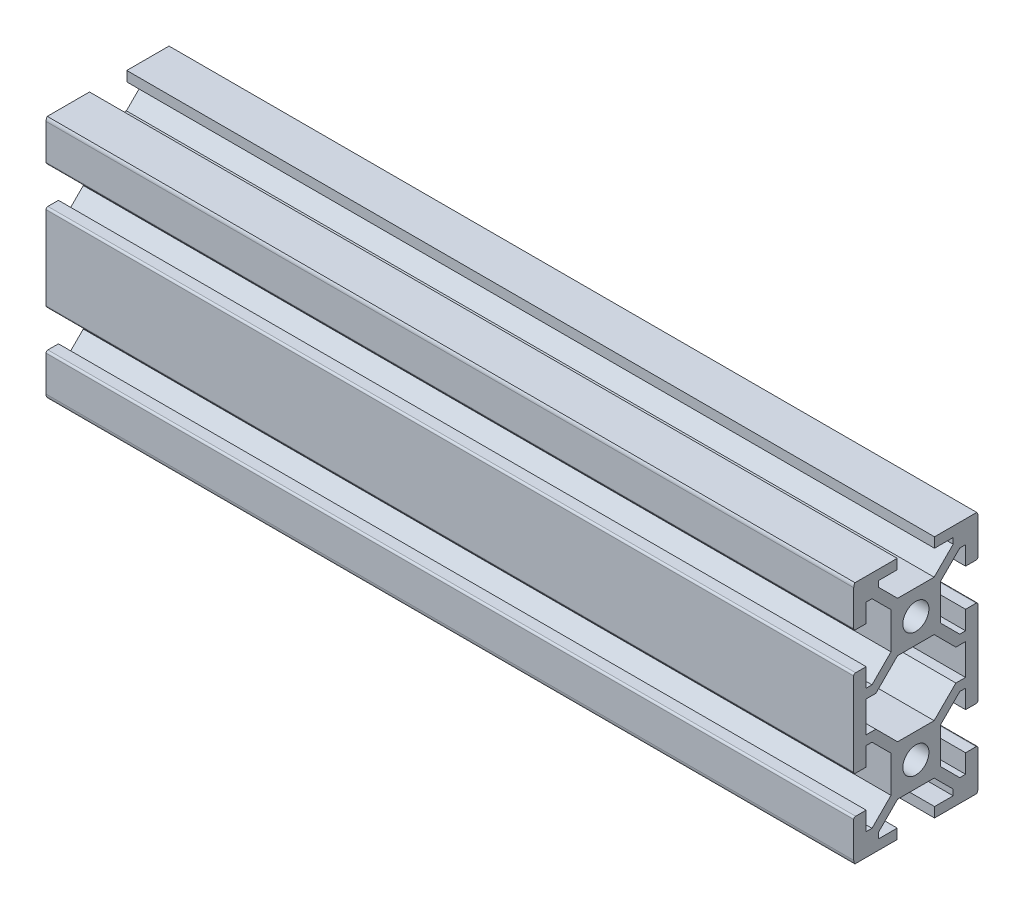
SolidWorks part; units mm, degrees
ref_plane "Front Plane" through (0, 0, 0) normal (0, 0, 1) x (1, 0, 0)
ref_plane "Top Plane" through (0, 0, 0) normal (0, 1, 0) x (1, 0, 0)
ref_plane "Right Plane" through (0, 0, 0) normal (1, 0, 0) x (0, 0, -1)
sketch "Sketch1" plane through (0, 0, 0) normal (0, 1, 0) x (1, 0, 0)
  line L0 (0, 0) -> (130, 0)
  dimension "D1" = 130
other "Seri 5 (20,40) 20X40S5(2)"
ref_plane "Plane1" through (0, 0, 0) normal (1, 0, 0) x (0, 0, -1)
sketch "草图1" plane through (0, 0, 0) normal (1, 0, 0) x (0, 0, -1)
  line L0 (-10, 19) -> (-10, 13.3)
  line L1 (-9.7, 13) -> (-8, 13)
  line L2 (-8, 13) -> (-8, 16)
  line L3 (-8, 16) -> (-7.0607, 16)
  line L4 (-7.0607, 16) -> (-4, 12.9393)
  line L5 (-4, 12.9393) -> (-4, 7.0607)
  line L6 (-4, 7.0607) -> (-7.0607, 4)
  line L7 (-7.0607, 4) -> (-8, 4)
  line L8 (-8, 4) -> (-8, 7)
  line L9 (-8, 7) -> (-9.7, 7)
  line L10 (-10, 6.7) -> (-10, -6.7)
  line L11 (-9.7, -7) -> (-8, -7)
  line L12 (-8, -7) -> (-8, -4)
  line L13 (-8, -4) -> (-7.0607, -4)
  line L14 (-7.0607, -4) -> (-4, -7.0607)
  line L15 (-4, -7.0607) -> (-4, -12.9393)
  line L16 (-4, -12.9393) -> (-7.0607, -16)
  line L17 (-7.0607, -16) -> (-8, -16)
  line L18 (-8, -16) -> (-8, -13)
  line L19 (-8, -13) -> (-9.7, -13)
  line L20 (-10, -13.3) -> (-10, -19)
  line L21 (-9.8, -19.6) -> (-3, -19.6)
  line L22 (-3, -19.6) -> (-3, -18)
  line L23 (-3, -18) -> (-6, -18)
  line L24 (-6, -18) -> (-6, -17.0607)
  line L25 (-6, -17.0607) -> (-2.9393, -14)
  line L26 (-2.9393, -14) -> (2.9393, -14)
  line L27 (2.9393, -14) -> (6, -17.0607)
  line L28 (6, -17.0607) -> (6, -18)
  line L29 (6, -18) -> (3, -18)
  line L30 (3, -18) -> (3, -19.6)
  line L31 (3, -19.6) -> (9.8, -19.6)
  line L32 (10, -19) -> (10, -13.3)
  line L33 (9.7, -13) -> (8, -13)
  line L34 (8, -13) -> (8, -16)
  line L35 (8, -16) -> (7.0607, -16)
  line L36 (7.0607, -16) -> (4, -12.9393)
  line L37 (4, -12.9393) -> (4, -7.0607)
  line L38 (4, -7.0607) -> (7.0607, -4)
  line L39 (7.0607, -4) -> (8, -4)
  line L40 (8, -4) -> (8, -7)
  line L41 (8, -7) -> (9.7, -7)
  line L42 (10, -6.7) -> (10, 6.7)
  line L43 (9.7, 7) -> (8, 7)
  line L44 (8, 7) -> (8, 4)
  line L45 (8, 4) -> (7.0607, 4)
  line L46 (7.0607, 4) -> (4, 7.0607)
  line L47 (4, 7.0607) -> (4, 12.9393)
  line L48 (4, 12.9393) -> (7.0607, 16)
  line L49 (7.0607, 16) -> (8, 16)
  line L50 (8, 16) -> (8, 13)
  line L51 (8, 13) -> (9.7, 13)
  line L52 (10, 13.3) -> (10, 19)
  line L53 (9.8, 19.6) -> (3, 19.6)
  line L54 (3, 19.6) -> (3, 18)
  line L55 (3, 18) -> (6, 18)
  line L56 (6, 18) -> (6, 17.0607)
  line L57 (6, 17.0607) -> (2.9393, 14)
  line L58 (2.9393, 14) -> (-2.9393, 14)
  line L59 (-2.9393, 14) -> (-6, 17.0607)
  line L60 (-6, 17.0607) -> (-6, 18)
  line L61 (-6, 18) -> (-3, 18)
  line L62 (-3, 18) -> (-3, 19.6)
  line L63 (-3, 19.6) -> (-9.8, 19.6)
  line L64 (-8, -2.5) -> (-6.4393, -2.5)
  line L65 (-6.4393, -2.5) -> (-2.9393, -6)
  line L66 (-2.9393, -6) -> (2.9393, -6)
  line L67 (2.9393, -6) -> (6.4393, -2.5)
  line L68 (6.4393, -2.5) -> (8, -2.5)
  line L69 (8, -2.5) -> (8, 2.5)
  line L70 (8, 2.5) -> (6.4393, 2.5)
  line L71 (6.4393, 2.5) -> (2.9393, 6)
  line L72 (2.9393, 6) -> (-2.9393, 6)
  line L73 (-2.9393, 6) -> (-6.4393, 2.5)
  line L74 (-6.4393, 2.5) -> (-8, 2.5)
  line L75 (-8, 2.5) -> (-8, -2.5)
  arc A0 (-10, 13.3) -> (-9.7, 13) centre (-9.7, 13.3) ccw
  arc A1 (-9.7, 7) -> (-10, 6.7) centre (-9.7, 6.7) ccw
  arc A2 (-10, -6.7) -> (-9.7, -7) centre (-9.7, -6.7) ccw
  arc A3 (-9.7, -13) -> (-10, -13.3) centre (-9.7, -13.3) ccw
  arc A4 (-10, -19) -> (-9.8, -19.6) centre (-9, -19) ccw
  arc A5 (9.8, -19.6) -> (10, -19) centre (9, -19) ccw
  arc A6 (10, -13.3) -> (9.7, -13) centre (9.7, -13.3) ccw
  arc A7 (9.7, -7) -> (10, -6.7) centre (9.7, -6.7) ccw
  arc A8 (10, 6.7) -> (9.7, 7) centre (9.7, 6.7) ccw
  arc A9 (9.7, 13) -> (10, 13.3) centre (9.7, 13.3) ccw
  arc A10 (10, 19) -> (9.8, 19.6) centre (9, 19) ccw
  arc A11 (-9.8, 19.6) -> (-10, 19) centre (-9, 19) ccw
  circle A12 centre (0, -10) radius 2.1
  circle A13 centre (0, 10) radius 2.1
  point P104 (-10, 19.6)
  point P105 (0, 19.6)
  point P106 (10, 19.6)
  point P107 (10, 10)
  point P108 (10, -10)
  point P109 (10, -19.6)
  point P110 (0, -19.6)
  point P111 (-10, -19.6)
  point P112 (-10, -10)
  point P113 (-10, 10)
  point P114 (-10, 0)
  point P115 (10, 0)
  point P116 (0, 0)
